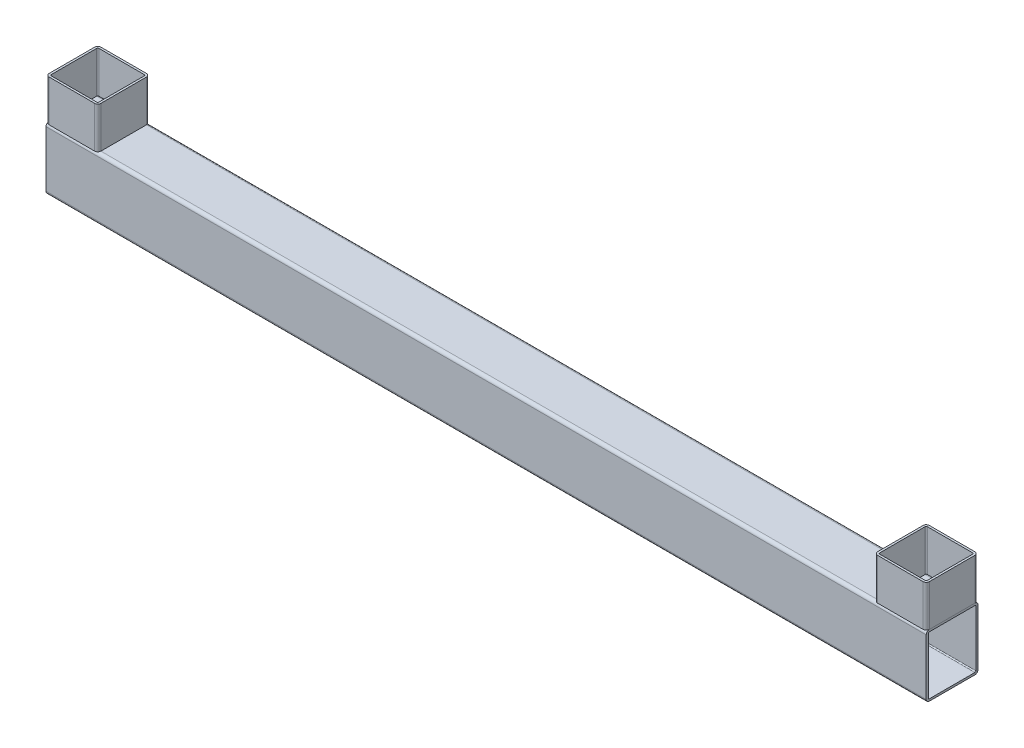
SolidWorks part; units mm, degrees
material "1.0037 (S235JR)"
ref_plane "Płaszczyzna przednia" through (0, 0, 0) normal (0, 0, 1) x (1, 0, 0)
ref_plane "Płaszczyzna górna" through (0, 0, 0) normal (0, 1, 0) x (1, 0, 0)
ref_plane "Płaszczyzna prawa" through (0, 0, 0) normal (1, 0, 0) x (0, 0, -1)
sketch "Szkic1" plane through (0, 0, 0) normal (1, 0, 0) x (0, 0, -1)
  line L0 (-44, 56) -> (44, 56)
  line L1 (-44, 60) -> (44, 60)
  line L2 (-50, 54) -> (-50, -54)
  line L3 (-44, -60) -> (44, -60)
  line L4 (50, 54) -> (50, -54)
  line L5 (-50, 60) -> (50, -60) construction
  line L6 (-50, -60) -> (50, 60) construction
  line L7 (46, 54) -> (46, -54)
  line L8 (-44, -56) -> (44, -56)
  line L9 (-46, 54) -> (-46, -54)
  arc A0 (44, 60) -> (50, 54) centre (44, 54) cw
  arc A1 (-50, -54) -> (-44, -60) centre (-44, -54) ccw
  arc A2 (-44, 60) -> (-50, 54) centre (-44, 54) ccw
  arc A3 (44, -60) -> (50, -54) centre (44, -54) ccw
  arc A4 (44, 56) -> (46, 54) centre (44, 54) cw
  arc A5 (44, -56) -> (46, -54) centre (44, -54) ccw
  arc A6 (-46, -54) -> (-44, -56) centre (-44, -54) ccw
  arc A7 (-44, 56) -> (-46, 54) centre (-44, 54) ccw
  point P0 (0, 0)
  dimension "D3" = 6
  dimension "D1" = 120
  dimension "D2" = 100
  dimension "D4" = 4
extrude "Dodanie-wyciągnięcie1" add sketch "Szkic1" along normal blind 1700
sketch "Szkic2" plane through (0, 60, 0) normal (0, 1, 0) x (1, 0, 0)
  line L0 (1606, 46) -> (1694, 46)
  line L1 (1606, 50) -> (1694, 50)
  line L2 (1600, 44) -> (1600, -44)
  line L3 (1606, -50) -> (1694, -50)
  line L4 (1700, 44) -> (1700, -44)
  line L5 (1600, 50) -> (1700, -50) construction
  line L6 (1600, -50) -> (1700, 50) construction
  line L7 (1696, 44) -> (1696, -44)
  line L8 (1606, -46) -> (1694, -46)
  line L9 (1604, 44) -> (1604, -44)
  line L10 (1700, 44) -> (1700, -44) construction
  line L11 (1700, 50) -> (0, 50) construction
  arc A0 (1694, 50) -> (1700, 44) centre (1694, 44) cw
  arc A1 (1600, -44) -> (1606, -50) centre (1606, -44) ccw
  arc A2 (1606, 50) -> (1600, 44) centre (1606, 44) ccw
  arc A3 (1694, -50) -> (1700, -44) centre (1694, -44) ccw
  arc A4 (1694, 46) -> (1696, 44) centre (1694, 44) cw
  arc A5 (1694, -46) -> (1696, -44) centre (1694, -44) ccw
  arc A6 (1604, -44) -> (1606, -46) centre (1606, -44) ccw
  arc A7 (1606, 46) -> (1604, 44) centre (1606, 44) ccw
  point P0 (1650, 0)
  point P43 (1700, 0)
  dimension "D5" = 6
  dimension "D1" = 4
  dimension "D2" = 4
  dimension "D3" = 4
  dimension "D4" = 4
  dimension "D7" = 100
extrude "Dodanie-wyciągnięcie2" add sketch "Szkic2" along normal blind 80 separate body
ref_plane "Płaszczyzna1" through (850, 0, 0) normal (-1, 0, 0) x (0, 0, 1)
mirror "Lustro3" about plane through (850, 0, 0) normal (-1, 0, 0) of bodies 102
